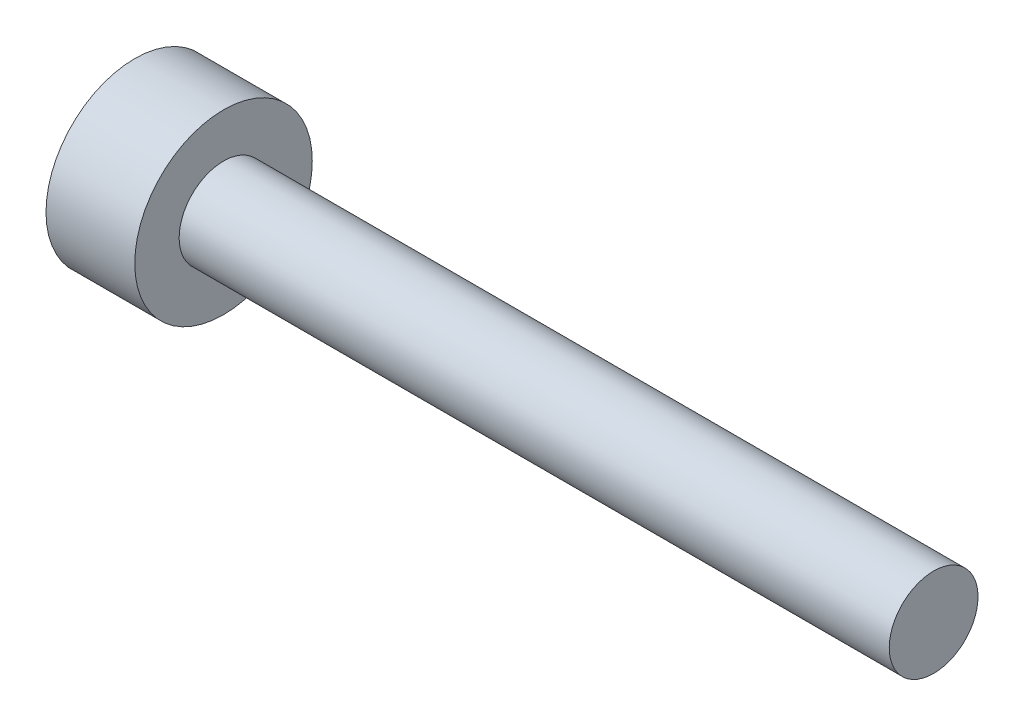
SolidWorks part; units mm, degrees
ref_plane "Front Plane" through (0, 0, 0) normal (0, 0, 1) x (1, 0, 0)
ref_plane "Top Plane" through (0, 0, 0) normal (0, 1, 0) x (1, 0, 0)
ref_plane "Right Plane" through (0, 0, 0) normal (1, 0, 0) x (0, 0, -1)
sketch "Sketch1" plane through (0, 0, 0) normal (1, 0, 0) x (0, 0, -1)
  circle A0 centre (0, 0) radius 2.5
  dimension "D1" = 5
extrude "Boss-Extrude1" add sketch "Sketch1" along normal blind 40
sketch "Sketch2" plane through (0, 0, 0) normal (-1, 0, 0) x (0, 0, 1)
  circle A0 centre (0, 0) radius 5
  dimension "D1" = 10
extrude "Boss-Extrude2" add sketch "Sketch2" along normal blind 5
